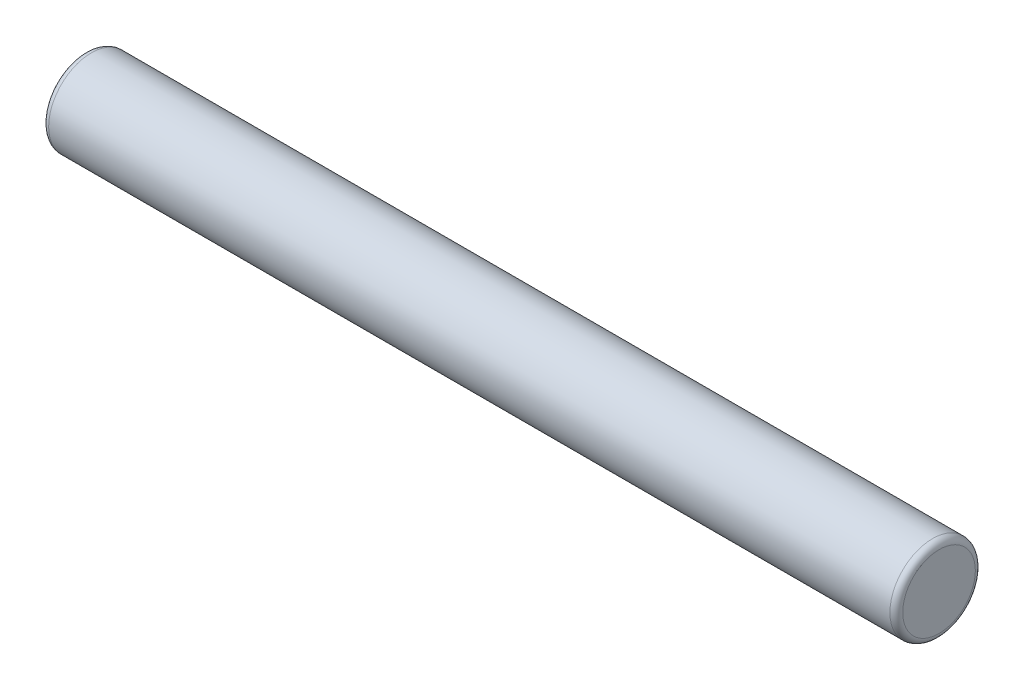
SolidWorks part; units mm, degrees
ref_plane "Plan de face" through (0, 0, 0) normal (0, 0, 1) x (1, 0, 0)
ref_plane "Plan de dessus" through (0, 0, 0) normal (0, 1, 0) x (1, 0, 0)
ref_plane "Plan de droite" through (0, 0, 0) normal (1, 0, 0) x (0, 0, -1)
sketch "Esquisse2" plane through (0, 0, 0) normal (0, 0, 1) x (1, 0, 0)
  line L1 (0, 0) -> (40, 0)
  line L2 (0, 0) -> (0, 2)
  line L3 (0, 2) -> (40, 2)
  line L4 (40, 0) -> (40, 2)
  dimension "D1" = 2
  dimension "D2" = 40
revolve "Révolution1" add sketch "Esquisse2" angle 360 about L3
fillet "Congé1" radius 0.3 2 edges at (0, 2, 2) (40, 2, 2)
